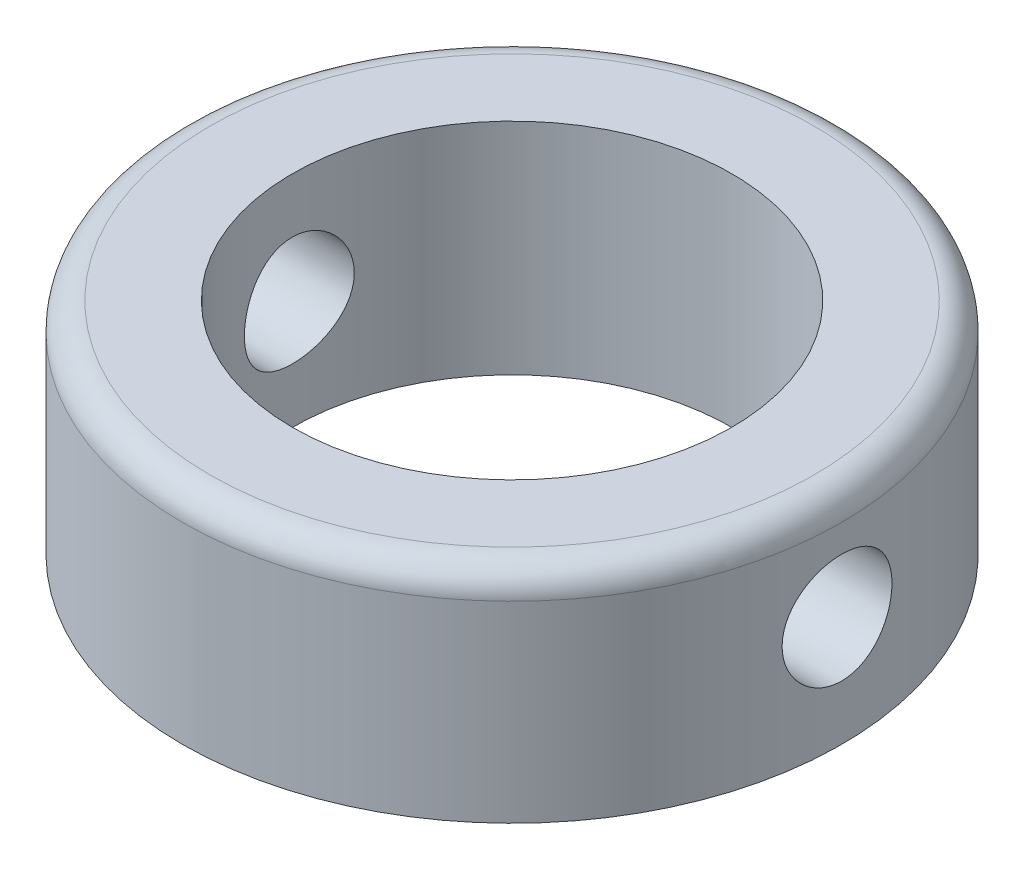
SolidWorks part; units mm, degrees
ref_plane "Front Plane" through (0, 0, 0) normal (0, 0, 1) x (1, 0, 0)
ref_plane "Top Plane" through (0, 0, 0) normal (0, 1, 0) x (1, 0, 0)
ref_plane "Right Plane" through (0, 0, 0) normal (1, 0, 0) x (0, 0, -1)
sketch "Sketch1" plane through (0, 0, 0) normal (0, 1, 0) x (1, 0, 0)
  circle A0 centre (0, 0) radius 8
  circle A1 centre (0, 0) radius 12
  dimension "D1" = 16
  dimension "D2" = 24
extrude "Boss-Extrude1" add sketch "Sketch1" along normal mid plane 8
fillet "Fillet1" radius 1 1 edges at (0, 4, 12)
sketch "Sketch2" plane through (0, 0, 0) normal (1, 0, 0) x (0, 0, -1)
  circle A0 centre (0, 0) radius 2
  dimension "D1" = 4
extrude "Cut-Extrude1" cut sketch "Sketch2" against normal through all both and the other way through all
